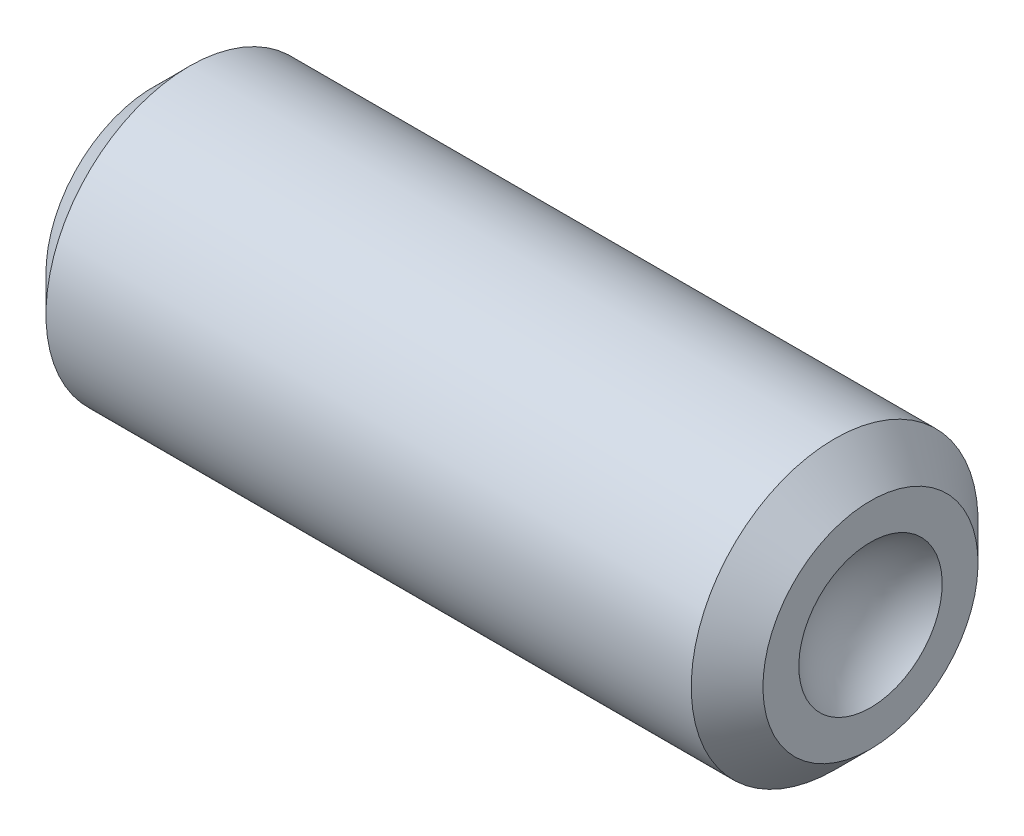
SolidWorks part; units mm, degrees
ref_plane "Front Plane" through (0, 0, 0) normal (0, 0, 1) x (1, 0, 0)
ref_plane "Top Plane" through (0, 0, 0) normal (0, 1, 0) x (1, 0, 0)
ref_plane "Right Plane" through (0, 0, 0) normal (1, 0, 0) x (0, 0, -1)
sketch "Sketch1" plane through (0, 0, 0) normal (0, 0, 1) x (1, 0, 0)
  line L0 (0, 0) -> (0, 1.5)
  line L1 (0, 1.5) -> (0.5, 2)
  line L2 (0.5, 2) -> (9.5, 2)
  line L3 (9.5, 2) -> (10, 1.5)
  line L4 (0, 0) -> (9.5, 0) construction
  line L5 (0.5, 2) -> (0.5, 1.5) construction
  line L6 (0.5, 1.5) -> (0.5, 1) construction
  line L7 (0.5, 1) -> (0.5, 0.5) construction
  line L8 (0.5, 0.5) -> (0.5, 0) construction
  line L9 (0.5, 1.5) -> (0, 1.5) construction
  line L10 (9.5, 2) -> (9.5, 0) construction
  line L11 (10, 1.5) -> (10, 1)
  line L12 (0, 0) -> (9.5, 0)
  arc A0 (9.5, 0) -> (10, 1) centre (10.75, 0) cw
  dimension "D1" = 45
  dimension "D2" = 4
  dimension "D3" = 10
  dimension "D4" = 2
revolve "Revolve1" add sketch "Sketch1" angle 360 about L12
sketch "Sketch2" plane through (0, 0, 0) normal (-1, 0, 0) x (0, 0, 1)
  line L1 (0, 1.1547) -> (-1, 0.5774)
  line L2 (-1, 0.5774) -> (-1, -0.5774)
  line L3 (-1, -0.5774) -> (0, -1.1547)
  line L4 (0, -1.1547) -> (1, -0.5774)
  line L5 (1, -0.5774) -> (1, 0.5774)
  line L6 (1, 0.5774) -> (0, 1.1547)
  circle A0 centre (0, 0) radius 1 construction
  dimension "D1" = 2
extrude "Cut-Extrude1" cut sketch "Sketch2" against normal offset from surface (8 mm away) 2 up to face at (10, -1.5, 0)
